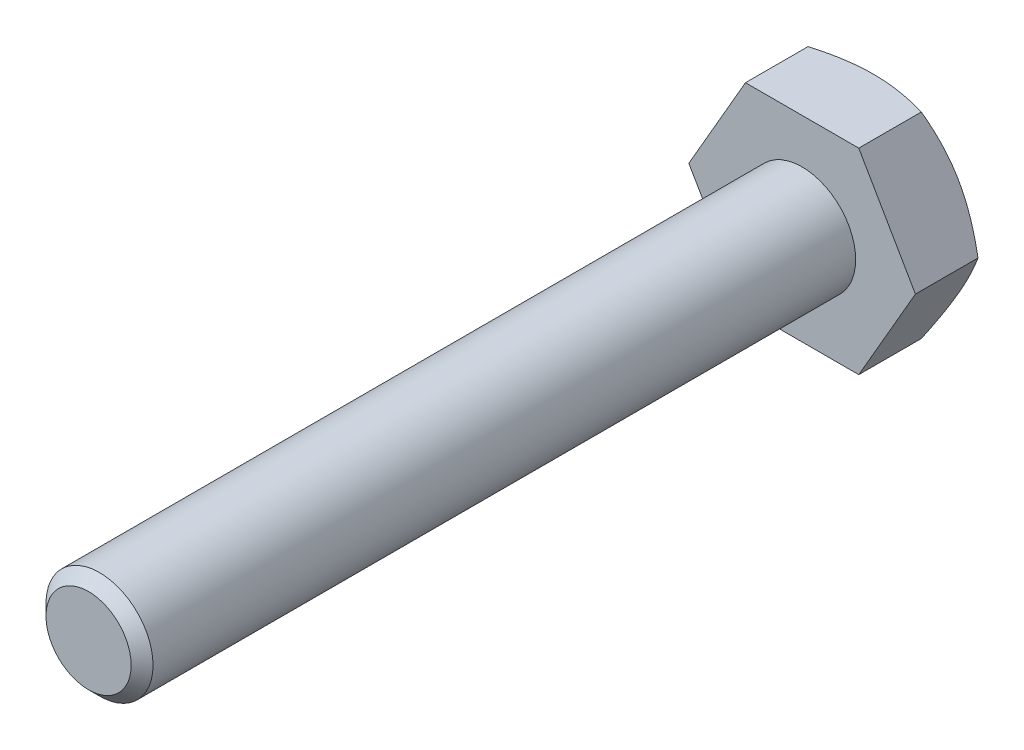
SolidWorks part; units mm, degrees
material "Plain Carbon Steel"
ref_plane "Front Plane" through (0, 0, 0) normal (0, 0, 1) x (1, 0, 0)
ref_plane "Top Plane" through (0, 0, 0) normal (0, 1, 0) x (1, 0, 0)
ref_plane "Right Plane" through (0, 0, 0) normal (1, 0, 0) x (0, 0, -1)
sketch "Sketch1" plane through (0, 0, 0) normal (0, 0, 1) x (1, 0, 0)
  line L1 (3.1754, 0) -> (1.5877, 2.75)
  line L2 (1.5877, 2.75) -> (-1.5877, 2.75)
  line L3 (-1.5877, 2.75) -> (-3.1754, 0)
  line L4 (-3.1754, 0) -> (-1.5877, -2.75)
  line L5 (-1.5877, -2.75) -> (1.5877, -2.75)
  line L6 (1.5877, -2.75) -> (3.1754, 0)
  circle A0 centre (0, 0) radius 2.75 construction
  dimension "D1" = 5.5
extrude "Extrude1" add sketch "Sketch1" along normal blind 2
sketch "Sketch2" plane through (0, 0, 2) normal (0, 0, 1) x (1, 0, 0)
  circle A0 centre (0, 0) radius 1.5
  dimension "D1" = 3
extrude "Extrude2" add sketch "Sketch2" along normal blind 20
cosmetic thread "Cosmetic Thread1" parameters "D2"=2.386
sketch "Sketch3" plane through (0, 0, 0) normal (1, 0, 0) x (0, 0, -1)
  line L0 (0, 2.75) -> (0, 102.75)
  line L1 (0, 102.75) -> (-57.735, 102.75)
  line L2 (-57.735, 102.75) -> (0, 2.75)
  line L3 (0, 0) -> (11.4679, 0) construction
  dimension "D1" = 30
  dimension "D2" = 100
revolve "Cut-Revolve1" cut sketch "Sketch3" angle 360 about L3
chamfer "Chamfer1" distance 0.307 angle 45 1 edges at (1.5, 0, 22)
